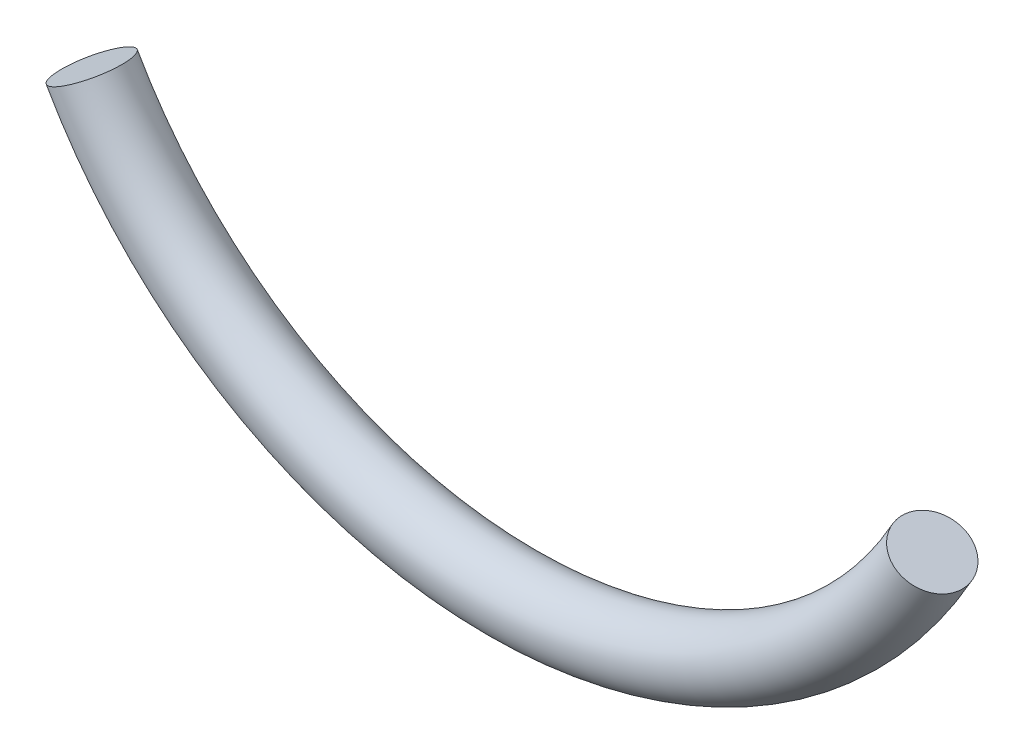
SolidWorks part; units mm, degrees
material "Custom Plastic"
ref_plane "X-Y Datum" through (0, 0, 0) normal (0, 0, 1) x (1, 0, 0)
ref_plane "X-Z Datum" through (0, 0, 0) normal (0, 1, 0) x (1, 0, 0)
ref_plane "Y-Z Datum" through (0, 0, 0) normal (1, 0, 0) x (0, 0, -1)
sketch3d "3DSketch1"
  arc A0 (-174.9238, -109.8415, 219.825) -> (-97.5042, -109.8415, 219.825) centre (-136.214, -87.9932, 219.825) cw
  circle A1 centre (-174.9238, -109.8415, 219.825) radius 4.5 construction
  circle A2 centre (-97.5042, -109.8415, 219.825) radius 4.5 construction
  point P2 (-136.214, -87.9932, 264.275)
  point P7 (-171.7419, -113.0235, 219.825)
  point P10 (-100.6861, -113.0235, 219.825)
  dimension "D1" = 44.45
sweep "Sweep1" add path "3DSketch1" circular profile diameter 6.35 parameters "D3"=6.35
